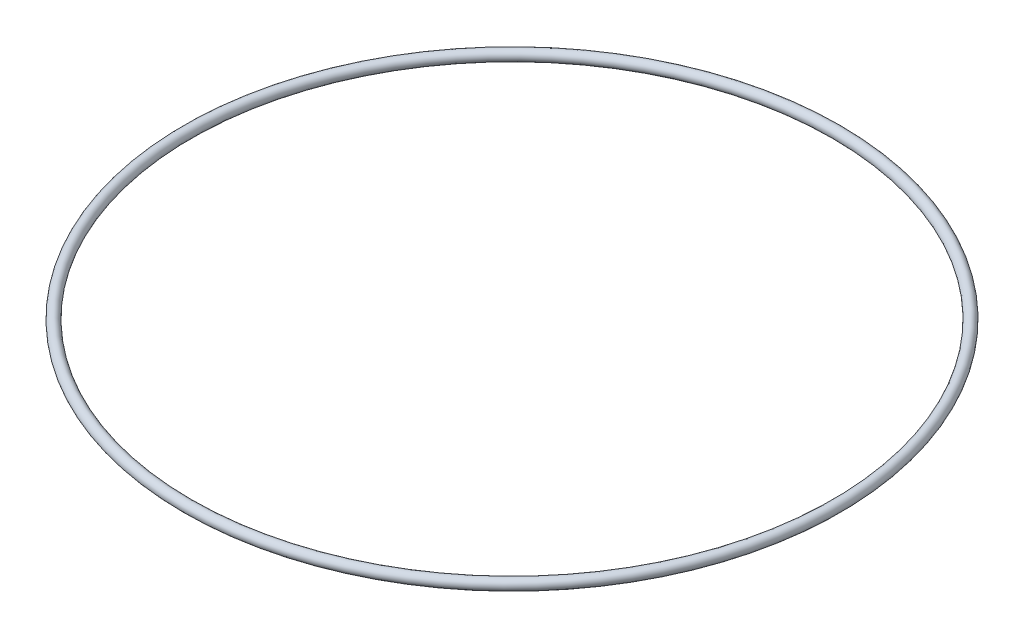
SolidWorks part; units mm, degrees
material "Silicon Rubber"
ref_plane "Front Plane" through (0, 0, 0) normal (0, 0, 1) x (1, 0, 0)
ref_plane "Top Plane" through (0, 0, 0) normal (0, 1, 0) x (1, 0, 0)
ref_plane "Right Plane" through (0, 0, 0) normal (1, 0, 0) x (0, 0, -1)
sketch "Sketch1" plane through (0, 0, 0) normal (0, 0, 1) x (1, 0, 0)
  line L0 (0, 0) -> (-96.8375, 0) construction
  line L1 (0, 0) -> (0, 31.5746) construction
  circle A0 centre (-96.8375, 0) radius 1.5875
  dimension "D2" = 3.175
  dimension "D1" = 96.8375
revolve "Revolve2" add sketch "Sketch1" angle 360 about L1
